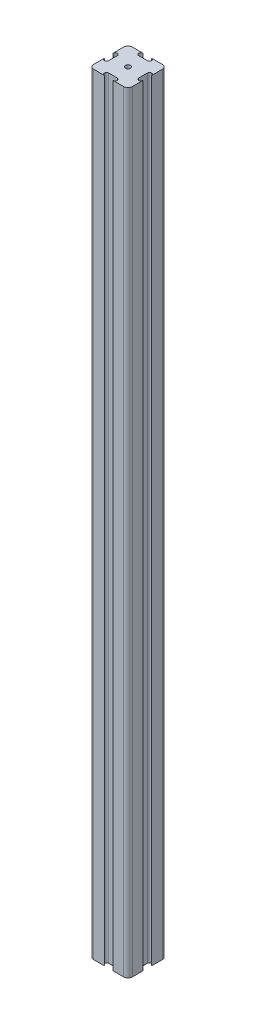
SolidWorks part; units mm, degrees
ref_plane "Front Plane" through (0, 0, 0) normal (0, 0, 1) x (1, 0, 0)
ref_plane "Top Plane" through (0, 0, 0) normal (0, 1, 0) x (1, 0, 0)
ref_plane "Right Plane" through (0, 0, 0) normal (1, 0, 0) x (0, 0, -1)
sketch "Esquisse4" plane through (0, 0, 0) normal (0, 1, 0) x (1, 0, 0)
  line L0 (-17.5, 22.5) -> (-5, 22.5)
  line L1 (22.5, 5) -> (22.5, 17.5)
  line L2 (0, 0) -> (22.5, 0) construction
  line L3 (5, 22.5) -> (17.5, 22.5)
  line L4 (0, 22.5) -> (0, 0) construction
  line L5 (-5, -17.5) -> (5, -17.5)
  line L6 (5, -22.5) -> (17.5, -22.5)
  line L7 (17.5, 5) -> (17.5, -5)
  line L8 (-5, -22.5) -> (-17.5, -22.5)
  line L10 (-5, 20) -> (5, 20) construction
  line L11 (0, 0) -> (0, -28.4326) construction
  line L12 (-5, 17.5) -> (5, 17.5)
  line L13 (17.5, 22.5) -> (17.5, -22.5) construction
  line L14 (-22.5, 17.5) -> (-22.5, 5)
  line L15 (-22.5, -5) -> (-22.5, -17.5)
  line L17 (-17.5, 5) -> (-17.5, -5)
  line L18 (0, 0) -> (-28.2169, 0) construction
  line L19 (22.5, -5) -> (22.5, -17.5)
  arc A0 (17.5, 22.5) -> (22.5, 17.5) centre (17.5, 17.5) cw
  arc A1 (17.5, -22.5) -> (22.5, -17.5) centre (17.5, -17.5) ccw
  arc A2 (-22.5, -17.5) -> (-17.5, -22.5) centre (-17.5, -17.5) ccw
  arc A3 (-17.5, 22.5) -> (-22.5, 17.5) centre (-17.5, 17.5) ccw
  arc A5 (-5, 22.5) -> (-5, 17.5) centre (-5, 20) ccw
  arc A6 (5, 17.5) -> (5, 22.5) centre (5, 20) ccw
  arc A7 (-5, -17.5) -> (-5, -22.5) centre (-5, -20) ccw
  arc A8 (5, -22.5) -> (5, -17.5) centre (5, -20) ccw
  arc A9 (-17.5, -5) -> (-22.5, -5) centre (-20, -5) cw
  arc A10 (22.5, -5) -> (17.5, -5) centre (20, -5) cw
  arc A11 (-17.5, 5) -> (-22.5, 5) centre (-20, 5) ccw
  arc A12 (22.5, 5) -> (17.5, 5) centre (20, 5) ccw
  point P8 (22.5, 22.5)
  point P13 (0, -17.5)
  point P20 (-22.5, 22.5)
  point P23 (0, 20)
  point P44 (0, 0)
  point P45 (0, 0)
  point P46 (0, 0)
  point P47 (28.2853, -8.4459)
  point P51 (0, 0)
  point P52 (0, 0)
  point P53 (-22.5, 5)
  point P54 (-17.5, 5)
  point P55 (-22.5, 5)
  point P56 (17.5, -7.7525)
  point P58 (0, 0)
  point P59 (22.5, -5)
  point P60 (17.5, 5)
  point P61 (22.5, 5)
  point P62 (20, -5)
  point P63 (17.5, -5)
  point P64 (22.5, -5)
  point P65 (17.5, 5)
  point P66 (22.5, 5)
  point P67 (22.5, -5)
  point P68 (17.5, -5)
  point P69 (0, 0)
  dimension "D4" = 5
  dimension "D6" = 5
  dimension "D7" = 5
  dimension "D8" = 5
  dimension "D20" = 10
  dimension "D24" = 12.5
  dimension "D2" = 22.5
  dimension "D3" = 45
  dimension "D5" = 10
  dimension "D10" = 10
  dimension "D11" = 12.5
  dimension "D12" = 22.5
  dimension "D13" = 5
  dimension "D14" = 17.5
  dimension "D15" = 12.5
  dimension "D16" = 45
  dimension "D17" = 2.5
  dimension "D18" = 5
  dimension "D19" = 45
  dimension "D21" = 5
  dimension "D22" = 17.5
  dimension "D23" = 10
  dimension "D25" = 5
extrude "Boss.-Extru.2" add sketch "Esquisse4" along normal blind 900 contours L15 A2 L8 A7 L5 A8 L6 A1 L19 A10 L7 A12 L1 A0 L3 A6 L12 A5 L0 A3 L14 A11 L17 A9
sketch "Esquisse5" plane through (0, 0, 0) normal (0, -1, 0) x (1, 0, 0)
  circle A0 centre (0, 0) radius 3
extrude "Enlèv. mat.-Extru.1" cut sketch "Esquisse5" against normal through all
